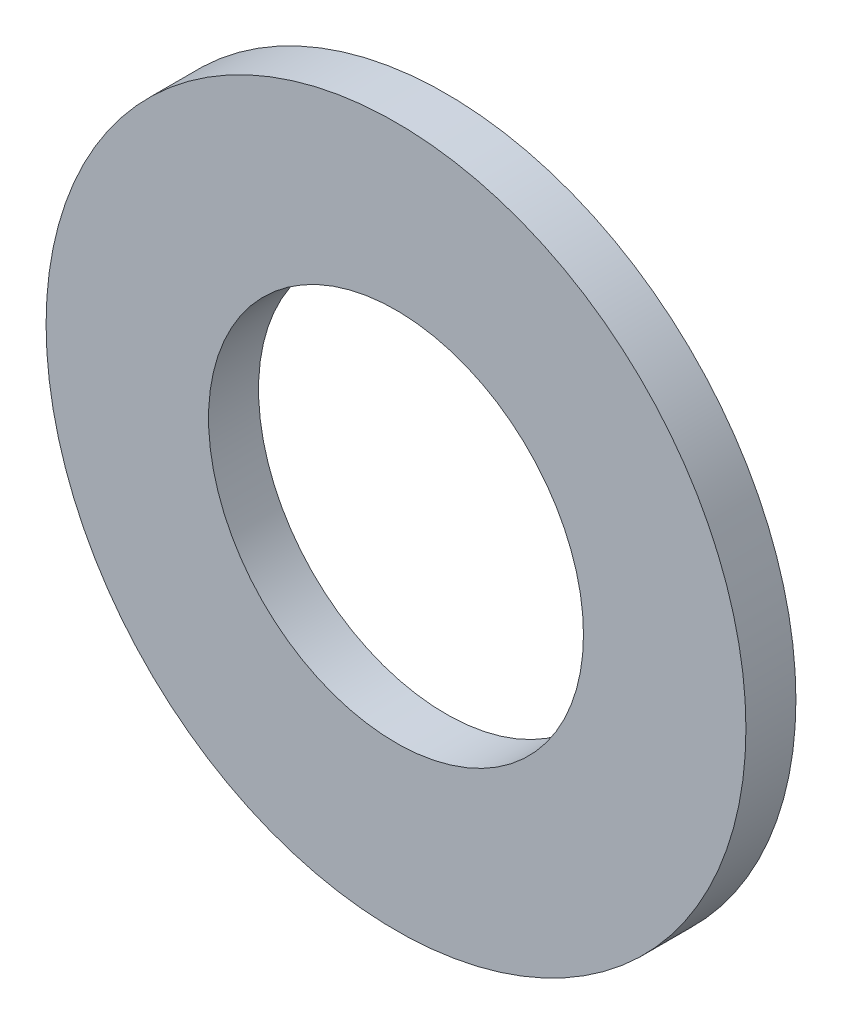
SolidWorks part; units mm, degrees
ref_plane "Front Plane" through (0, 0, 0) normal (0, 0, 1) x (1, 0, 0)
ref_plane "Top Plane" through (0, 0, 0) normal (0, 1, 0) x (1, 0, 0)
ref_plane "Right Plane" through (0, 0, 0) normal (1, 0, 0) x (0, 0, -1)
sketch "Sketch1" plane through (0, 0, 0) normal (0, 0, 1) x (1, 0, 0)
  circle A0 centre (0, 0) radius 7.5
  circle A1 centre (0, 0) radius 14
  dimension "D1" = 28
  dimension "D2" = 15
extrude "Boss-Extrude1" add sketch "Sketch1" along normal blind 2
